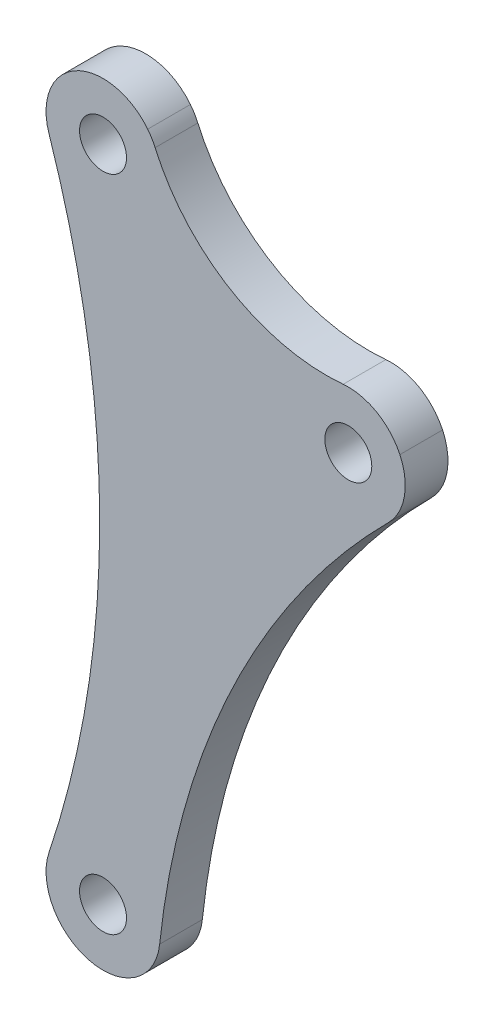
SolidWorks part; units mm, degrees
ref_plane "前视基准面" through (0, 0, 0) normal (0, 0, 1) x (1, 0, 0)
ref_plane "上视基准面" through (0, 0, 0) normal (0, 1, 0) x (1, 0, 0)
ref_plane "右视基准面" through (0, 0, 0) normal (1, 0, 0) x (0, 0, -1)
ref_plane "基准面4" through (0, 0, 0) normal (0, 0, -1) x (-1, 0, 0)
sketch "草图1" plane through (0, 0, 0) normal (0, 0, -1) x (-1, 0, 0)
  line L0 (3.3111, 16.0217) -> (3.3131, 16.0217)
  line L1 (3.295, 15.9735) -> (3.3111, 16.0217)
  arc A0 (3.3131, 16.0217) -> (-3.6194, 19.7723) centre (-0.4812, 17.2907) ccw
  arc A1 (-3.6194, 19.7723) -> (-4.1407, 18.9076) centre (-0.4812, 17.2907) ccw
  arc A2 (-4.1407, 18.9076) -> (-17.3517, 11.1206) centre (-16.1693, 24.2145) cw
  arc A3 (-17.3517, 11.1206) -> (-21.3337, 8.8326) centre (-17.709, 7.1333) ccw
  arc A4 (-21.3337, 8.8326) -> (-20.5427, 4.3096) centre (-17.7099, 7.1357) ccw
  arc A5 (-20.5427, 4.3096) -> (-4.4597, -29.3874) centre (-60.2315, -35.3197) cw
  arc A6 (-4.4597, -29.3874) -> (-1.8337, -32.7264) centre (-0.4826, -28.9616) ccw
  arc A7 (-1.8337, -32.7264) -> (2.3153, -31.8234) centre (-0.4798, -28.9642) ccw
  arc A8 (2.3153, -31.8234) -> (3.3133, -27.6934) centre (-0.4834, -28.9615) ccw
  arc A9 (3.3133, -27.6934) -> (3.295, 15.9735) centre (68.6418, -5.8326) cw
  circle A10 centre (-17.7114, 7.1362) radius 1.35
  circle A11 centre (-0.4809, -28.9628) radius 1.65
  circle A12 centre (-0.4809, 17.2912) radius 1.3
extrude "凸台-拉伸1" add sketch "草图1" against normal blind 3
sketch "草图2" plane through (0, 0, 3) normal (0, 0, 1) x (1, 0, 0)
  circle A0 centre (0.4809, 17.2912) radius 1.65
  circle A1 centre (17.7114, 7.1362) radius 1.65
  dimension "D1" = 3.3
extrude "切除-拉伸1" cut sketch "草图2" against normal through all
sketch "草图3" plane through (0, 0, 0) normal (0, 0, -1) x (-1, 0, 0)
  text T0 "10"
extrude "切除-拉伸2" cut sketch "草图3" against normal blind 1
